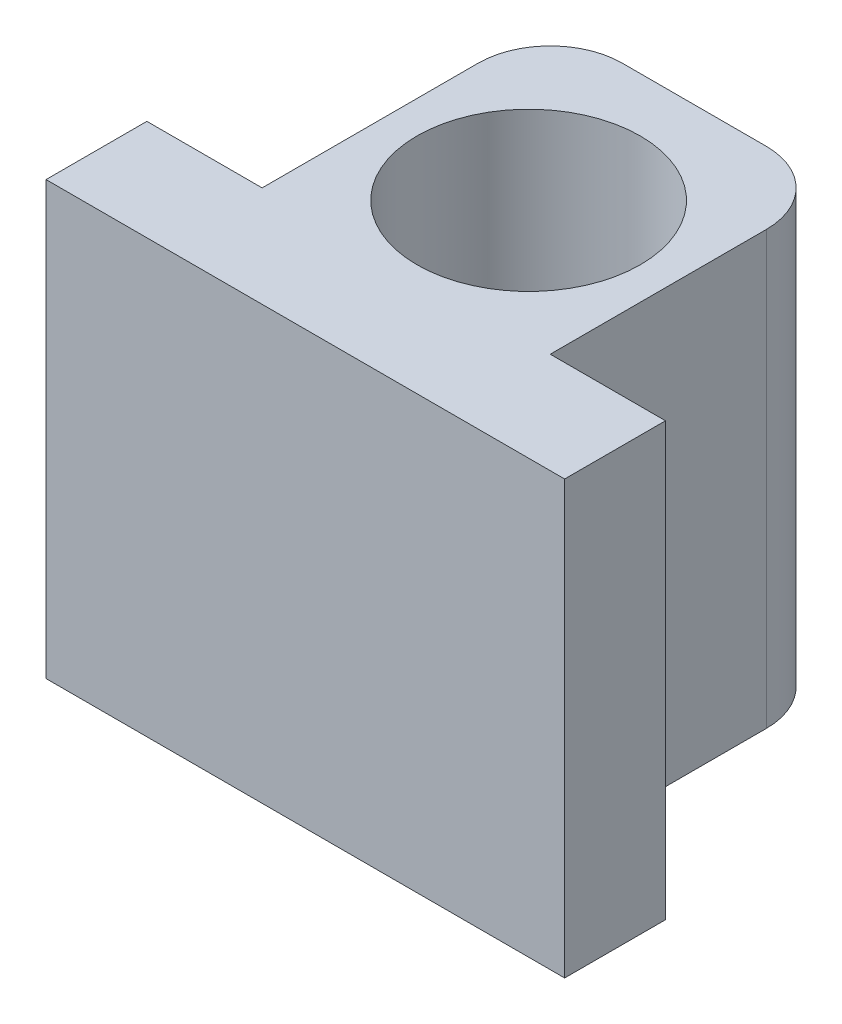
SolidWorks part; units mm, degrees
ref_plane "Front Plane" through (0, 0, 0) normal (0, 0, 1) x (1, 0, 0)
ref_plane "Top Plane" through (0, 0, 0) normal (0, 1, 0) x (1, 0, 0)
ref_plane "Right Plane" through (0, 0, 0) normal (1, 0, 0) x (0, 0, -1)
sketch "Sketch2" plane through (0, 0, 0) normal (0, 1, 0) x (1, 0, 0)
  line L0 (-14.8639, 0) -> (-6.8639, 0)
  line L1 (-6.8639, 0) -> (-6.8639, 20)
  line L2 (-6.8639, 20) -> (13.1361, 20)
  line L3 (13.1361, 20) -> (13.1361, 0)
  line L4 (13.1361, 0) -> (21.1361, 0)
  line L5 (21.1361, 0) -> (21.1361, -3)
  line L6 (21.1361, -3) -> (-14.8639, -3)
  line L7 (-14.8639, -3) -> (-14.8639, 0)
  dimension "D1" = 20
  dimension "D2" = 20
  dimension "D3" = 8
  dimension "D4" = 8
  dimension "D5" = 3
extrude "Boss-Extrude1" add sketch "Sketch2" along normal blind 30
sketch "Sketch3" plane through (0, 0, 0) normal (0, -1, 0) x (1, 0, 0)
  line L0 (3.1361, 3) -> (3.1361, -8.5) construction
  line L3 (-14.8639, 3) -> (21.1361, 3) construction
  circle A0 centre (3.1361, -8.5) radius 7.75
  dimension "D2" = 15.5
  dimension "D1" = 11.5
extrude "Cut-Extrude1" cut sketch "Sketch3" against normal blind 30
fillet "Fillet1" radius 5 2 edges at (13.1361, 15, -20) (-6.8639, 15, -20)
sketch "Sketch4" plane through (0, 0, 3) normal (0, 0, 1) x (1, 0, 0)
  line L1 (-14.8639, 30) -> (21.1361, 30)
  line L2 (-14.8639, 30) -> (-14.8639, 0)
  line L3 (-14.8639, 0) -> (21.1361, 0)
  line L4 (21.1361, 30) -> (21.1361, 0)
extrude "Boss-Extrude2" add sketch "Sketch4" along normal blind 4
